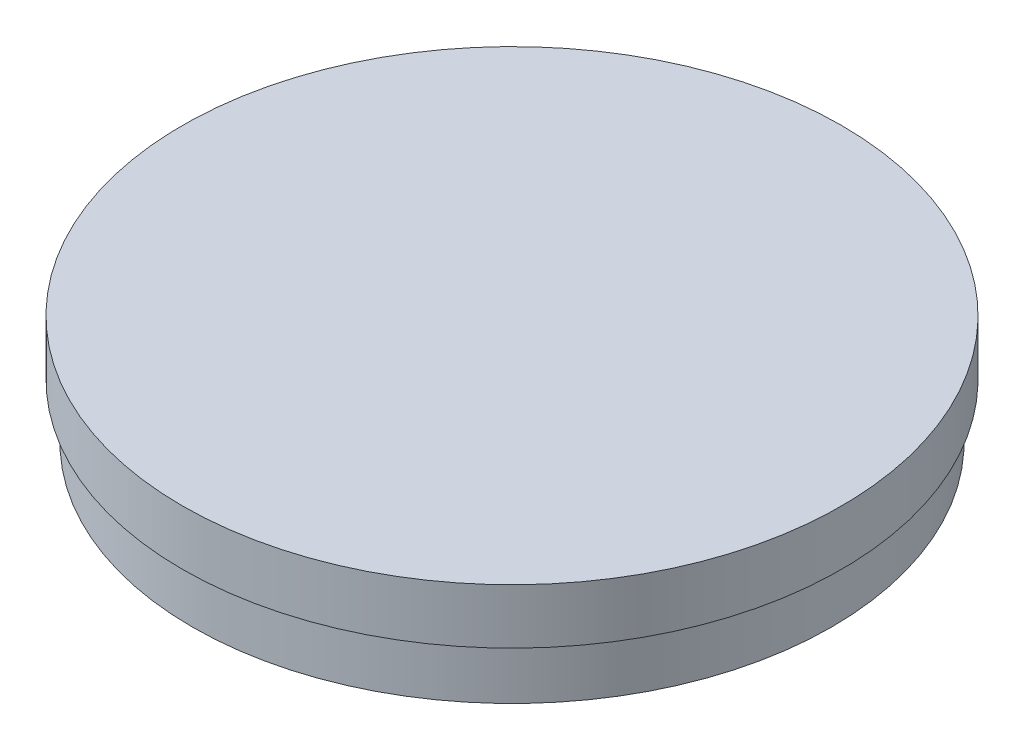
SolidWorks part; units mm, degrees
ref_plane "Front Plane" through (0, 0, 0) normal (0, 0, 1) x (1, 0, 0)
ref_plane "Top Plane" through (0, 0, 0) normal (0, 1, 0) x (1, 0, 0)
ref_plane "Right Plane" through (0, 0, 0) normal (1, 0, 0) x (0, 0, -1)
sketch "Sketch1" plane through (0, 0, 0) normal (0, 1, 0) x (1, 0, 0)
  circle A0 centre (0, 0) radius 76.2
  dimension "D1" = 152.4
extrude "Boss-Extrude1" add sketch "Sketch1" along normal blind 12.7
sketch "Sketch2" plane through (0, 0, 0) normal (0, -1, 0) x (1, 0, 0)
  circle A0 centre (0, 0) radius 73.914
  dimension "D1" = 147.828
extrude "Boss-Extrude2" add sketch "Sketch2" along normal blind 12.7
